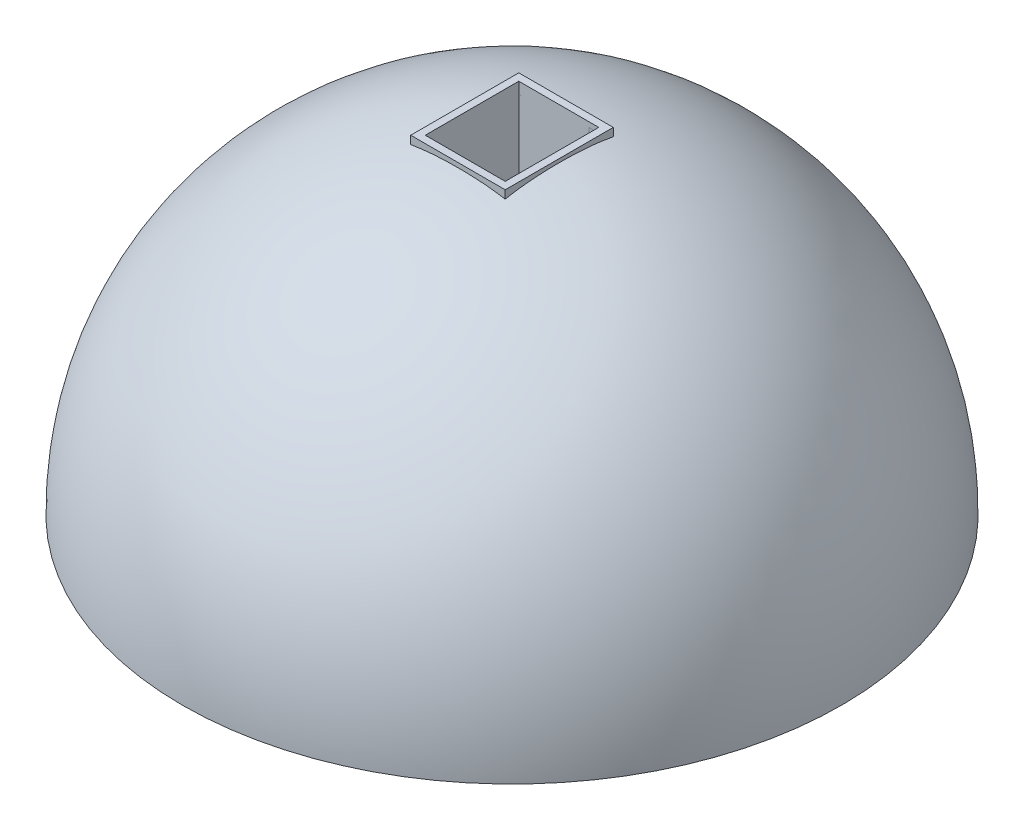
SolidWorks part; units mm, degrees
ref_plane "Front Plane" through (0, 0, 0) normal (0, 0, 1) x (1, 0, 0)
ref_plane "Top Plane" through (0, 0, 0) normal (0, 1, 0) x (1, 0, 0)
ref_plane "Right Plane" through (0, 0, 0) normal (1, 0, 0) x (0, 0, -1)
sketch "Sketch1" plane through (0, 0, 0) normal (0, 1, 0) x (1, 0, 0)
  line L0 (0, 13.812) -> (0, -13.42) construction
  line L1 (-8.25, 9.65) -> (8.25, 9.65)
  line L2 (-8.25, 9.65) -> (-8.25, -9.65)
  line L3 (-8.25, -9.65) -> (8.25, -9.65)
  line L4 (8.25, 9.65) -> (8.25, -9.65)
  line L5 (-15.3384, 0) -> (21.5933, 0) construction
  line L11 (-9.75, 11.15) -> (9.75, 11.15)
  line L12 (-9.75, 11.15) -> (-9.75, -11.15)
  line L13 (-9.75, -11.15) -> (9.75, -11.15)
  line L14 (9.75, 11.15) -> (9.75, -11.15)
  dimension "D1" = 16.5
  dimension "D2" = 19.3
  dimension "D3" = 1.5
  dimension "D4" = 1.5
extrude "Boss-Extrude1" add sketch "Sketch1" along normal blind 76.2
ref_plane "Plane1" through (0, 0, 0) normal (-1, 0, 0) x (0, 0, 1)
sketch "Sketch2" plane through (0, 0, 0) normal (-1, 0, 0) x (0, 0, 1)
  line L1 (0, 7.62) -> (0, -10.0902) construction
  line L2 (-23.2439, 7.62) -> (0, 7.62) construction
  line L5 (-65.5196, 7.62) -> (-68.0196, 7.62)
  line L6 (0, 73.7) -> (0, 76.2)
  line L7 (-11.15, 0) -> (11.15, 0) construction
  line L8 (-11.15, 76.2) -> (11.15, 76.2) construction
  arc A1 (0, 73.7) -> (-65.5196, 7.62) centre (0, 8.1781) ccw
  arc A3 (0, 76.2) -> (-68.0196, 7.62) centre (0, 8.1781) ccw
  point P6 (0, 0)
  point P15 (-65.1101, 27.8673)
  dimension "D1" = 7.62
  dimension "D4" = 2.5
revolve "Revolve1" add sketch "Sketch2" angle 360 about L1
sketch "Sketch3" plane through (0, 76.2, 0) normal (0, 1, 0) x (1, 0, 0)
  line L1 (-8.25, -9.65) -> (8.25, -9.65)
  line L2 (-8.25, -9.65) -> (-8.25, 9.65)
  line L3 (-8.25, 9.65) -> (8.25, 9.65)
  line L4 (8.25, -9.65) -> (8.25, 9.65)
extrude "Cut-Extrude1" cut sketch "Sketch3" against normal blind 25.4
sketch "Sketch4" plane through (9.75, 0, 0) normal (1, 0, 0) x (0, 0, -1)
  circle A0 centre (0, 24.5379) radius 1.75
  circle A1 centre (0, 52.0994) radius 1.75
  point P4 (0, 24.5379)
  point P5 (0, 52.0994)
  dimension "D1" = 3.5
extrude "Cut-Extrude2" cut sketch "Sketch4" against normal blind 12.7
sketch "Sketch5" plane through (0, 0, -11.15) normal (0, 0, -1) x (-1, 0, 0)
  line L0 (0, -12.265) -> (0, 12.265) construction
  circle A0 centre (0, 15.7258) radius 1.75
  circle A1 centre (0, 39.1971) radius 1.75
  dimension "D1" = 3.5
extrude "Cut-Extrude3" cut sketch "Sketch5" against normal blind 12.7
ref_plane "Plane2" through (0, 0, 0) normal (-0.7528, 0, -0.6583) x (-0.6583, 0, 0.7528)
